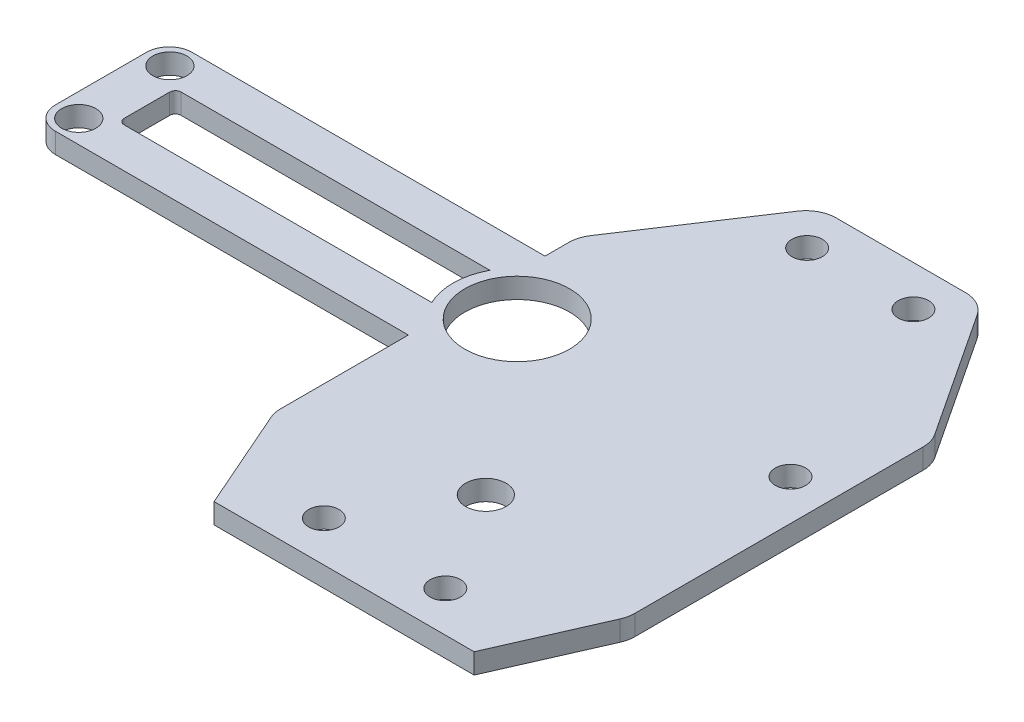
SolidWorks part; units mm, degrees
ref_plane "Alzado" through (0, 0, 0) normal (0, 0, 1) x (1, 0, 0)
ref_plane "Planta" through (0, 0, 0) normal (0, 1, 0) x (1, 0, 0)
ref_plane "Vista lateral" through (0, 0, 0) normal (1, 0, 0) x (0, 0, -1)
sketch "Croquis1" plane through (0, 0, 0) normal (0, 1, 0) x (1, 0, 0)
  line L0 (0, 0) -> (0, 62) construction
  line L2 (12.8466, 7) -> (17.5, 17.5997)
  line L3 (17.5, 17.5997) -> (17.5, 47.5997)
  line L4 (17.5, 47.5997) -> (8, 62)
  line L5 (8, 62) -> (-8, 62)
  line L6 (-12.8466, 7) -> (-17.5, 17.5997)
  line L7 (-17.5, 17.5997) -> (-17.5, 47.5997)
  line L8 (-17.5, 47.5997) -> (-8, 62)
  line L9 (-12.8466, 7) -> (12.8466, 7)
  line L10 (6.97, 22.2225) -> (17.5, 17.5997) construction
  line L11 (-5.25, 57.9943) -> (5.25, 57.9943) construction
  line L12 (-13.5, 37.5997) -> (13.5, 37.5997) construction
  line L16 (0, 39.0997) -> (0, 36.0997) construction
  line L17 (-6, 11) -> (6, 11) construction
  circle A0 centre (0, 21) radius 2
  circle A1 centre (-5.25, 57.9943) radius 1.5
  circle A2 centre (-13.5, 37.5997) radius 1.5
  circle A3 centre (13.5, 37.5997) radius 1.5
  circle A4 centre (5.25, 57.9943) radius 1.5
  circle A13 centre (-6, 11) radius 1.5
  circle A14 centre (6, 11) radius 1.5
  point P3 (0, 7)
  point P23 (0, 57.9943)
  point P24 (0, 37.5997)
  point P42 (0, 11)
  dimension "D7" = 4
  dimension "D8" = 4
  dimension "D9" = 10
  dimension "D10" = 3
  dimension "D20" = 12
  dimension "D1" = 62
  dimension "D2" = 35
  dimension "D3" = 7
  dimension "D4" = 16
  dimension "D5" = 30
  dimension "D11" = 10.5
  dimension "D12" = 27
  dimension "D13" = 22
  dimension "D14" = 10
extrude "Saliente-Extruir1" add sketch "Croquis1" along normal mid plane 2 contours L8 L5 L4 L3 L2 L6 L7
fillet "Redondeo1" radius 3 6 edges at (-8, 0, -62) (8, 0, -62) (17.5, 0, -47.5997) (17.5, 0, -17.5997) (-17.5, 0, -17.5997) (-17.5, 0, -47.5997)
scale "Scale1" scale about centroid uniform scaling yes scale factor 0.888889
sketch "Sketch1" plane through (0, -0.8889, 0) normal (0, -1, 0) x (1, 0, 0)
  line L0 (-12, -37.1351) -> (-46.5, -37.1351) construction
  line L1 (-46.5, -33.1351) -> (-46.5, -41.1351) construction
  line L2 (-46.5, -41.1351) -> (-15.5556, -41.1351) construction
  line L3 (-15.5556, -45.2236) -> (-15.5556, -19.9169) construction
  line L4 (-46.5, -33.1351) -> (-15.5556, -33.1351) construction
  line L5 (-15.5556, -31.1351) -> (-46.5556, -31.1351)
  line L6 (-48.5556, -33.1351) -> (-48.5556, -41.1351)
  line L7 (-46.5556, -43.1351) -> (-15.5556, -43.1351)
  line L8 (-15.5556, -43.1351) -> (-15.5556, -39.6351)
  line L9 (-15.5556, -39.6351) -> (-44.0139, -39.6351)
  line L10 (-44.5139, -39.1351) -> (-44.5139, -35.1351)
  line L11 (-44.0139, -34.6351) -> (-15.5556, -34.6351)
  line L12 (-15.5556, -34.6351) -> (-15.5556, -31.1351)
  circle A0 centre (-46.5, -33.1351) radius 1.5
  circle A1 centre (-46.5, -41.1351) radius 1.5
  arc A2 (-48.5556, -41.1351) -> (-46.5556, -43.1351) centre (-46.5556, -41.1351) ccw
  arc A3 (-46.5556, -31.1351) -> (-48.5556, -33.1351) centre (-46.5556, -33.1351) ccw
  arc A4 (-44.0139, -39.6351) -> (-44.5139, -39.1351) centre (-44.0139, -39.1351) cw
  arc A5 (-44.5139, -35.1351) -> (-44.0139, -34.6351) centre (-44.0139, -35.1351) cw
  point P27 (-48.5556, -43.1351)
  point P30 (-48.5556, -31.1351)
  point P33 (-44.5139, -39.6351)
  point P36 (-44.5139, -34.6351)
  dimension "D3" = 3
  dimension "D6" = 2
  dimension "D7" = 0.5
  dimension "D1" = 34.5
  dimension "D2" = 8
  dimension "D4" = 12
  dimension "D5" = 31
  dimension "D8" = 5
extrude "Boss-Extrude1" add sketch "Sketch1" against normal up to surface (1.7778 mm away) up to face at (-5.3333, 0.8889, -12.1576)
sketch "Sketch2" plane through (0, 0.8889, 0) normal (0, 1, 0) x (1, 0, 0)
  line L0 (-16.899, 39.6351) -> (-15.5556, 39.6351)
  line L1 (-15.5556, 39.6351) -> (-44.0139, 39.6351) construction
  line L2 (-15.5556, 39.6351) -> (-15.5556, 34.6351)
  line L3 (-15.5556, 34.6351) -> (-17.0004, 34.6351)
  line L4 (-44.0139, 34.6351) -> (-15.5556, 34.6351) construction
  arc A1 (-16.899, 39.6351) -> (-17.0004, 34.6351) centre (-12, 37.0348) ccw
extrude "Boss-Extrude2" add sketch "Sketch2" against normal up to surface (1.7778 mm away) up to face at (-11.1081, -0.8889, -36.877)
sketch "Sketch3" plane through (0, 0.8889, 0) normal (0, 1, 0) x (1, 0, 0)
  circle A0 centre (-12, 37.1351) radius 4.6
  dimension "D1" = 9.2
extrude "Cut-Extrude1" cut sketch "Sketch3" against normal blind 10
